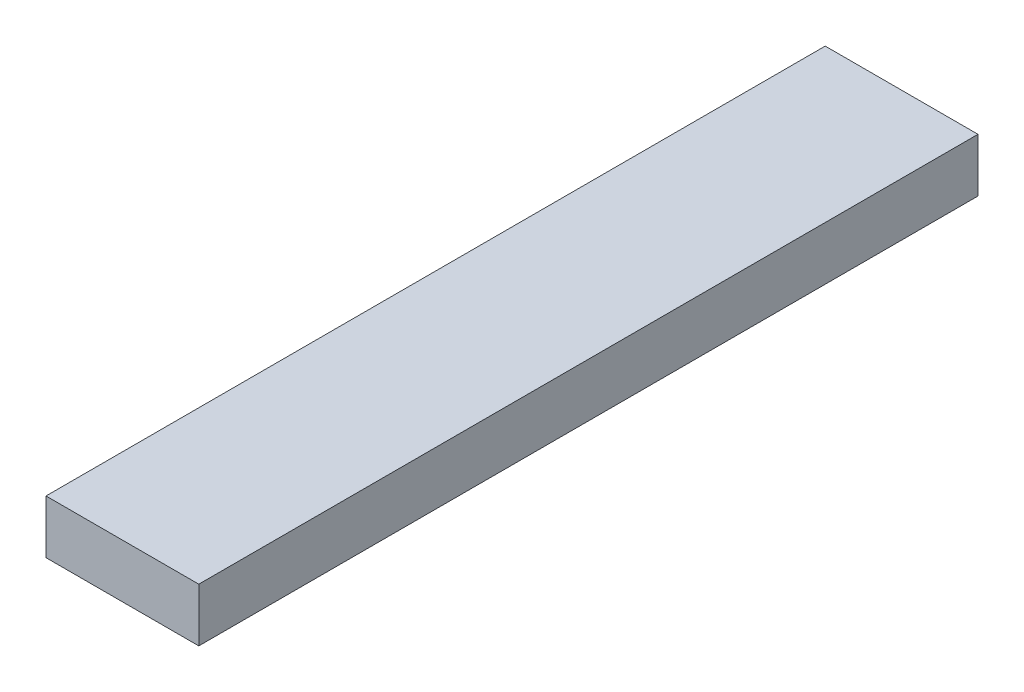
SolidWorks part; units mm, degrees
material "Сосна"
ref_plane "Спереди" through (0, 0, 0) normal (0, 0, 1) x (1, 0, 0)
ref_plane "Сверху" through (0, 0, 0) normal (0, 1, 0) x (1, 0, 0)
ref_plane "Справа" through (0, 0, 0) normal (1, 0, 0) x (0, 0, -1)
sketch "Эскиз1" plane through (0, 0, 0) normal (0, 0, 1) x (1, 0, 0)
  line L1 (0, 0) -> (100, 0)
  line L2 (0, 0) -> (0, 35)
  line L3 (0, 35) -> (100, 35)
  line L4 (100, 0) -> (100, 35)
  dimension "D1" = 35
  dimension "D2" = 100
extrude "Бобышка-Вытянуть1" add sketch "Эскиз1" against normal blind 510
